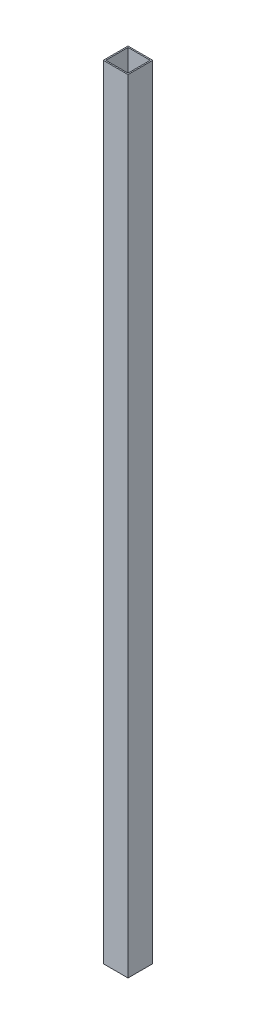
SolidWorks part; units mm, degrees
ref_plane "Front Plane" through (0, 0, 0) normal (0, 0, 1) x (1, 0, 0)
ref_plane "Top Plane" through (0, 0, 0) normal (0, 1, 0) x (1, 0, 0)
ref_plane "Right Plane" through (0, 0, 0) normal (1, 0, 0) x (0, 0, -1)
sketch "Sketch1" plane through (0, 0, 0) normal (0, 1, 0) x (1, 0, 0)
  line L1 (0, 0) -> (25.4, 0)
  line L2 (0, 0) -> (0, 25.4)
  line L3 (0, 25.4) -> (25.4, 25.4)
  line L4 (25.4, 0) -> (25.4, 25.4)
  dimension "D1" = 25.4
  dimension "D2" = 25.4
extrude "Boss-Extrude1" add sketch "Sketch1" along normal blind 803.275
sketch "Sketch3" plane through (0, 803.275, 0) normal (0, 1, 0) x (1, 0, 0)
  line L0 (25.4, 25.4) -> (0, 25.4) construction
  line L1 (24.13, 24.13) -> (1.27, 24.13)
  line L2 (24.13, 24.13) -> (24.13, 1.27)
  line L3 (24.13, 1.27) -> (1.27, 1.27)
  line L4 (1.27, 24.13) -> (1.27, 1.27)
  line L5 (25.4, 0) -> (25.4, 25.4) construction
  line L6 (0, 25.4) -> (0, 0) construction
  line L7 (0, 0) -> (25.4, 0) construction
  dimension "D1" = 1.27
  dimension "D2" = 1.27
  dimension "D3" = 1.27
  dimension "D4" = 1.27
extrude "Cut-Extrude1" cut sketch "Sketch3" against normal through all
